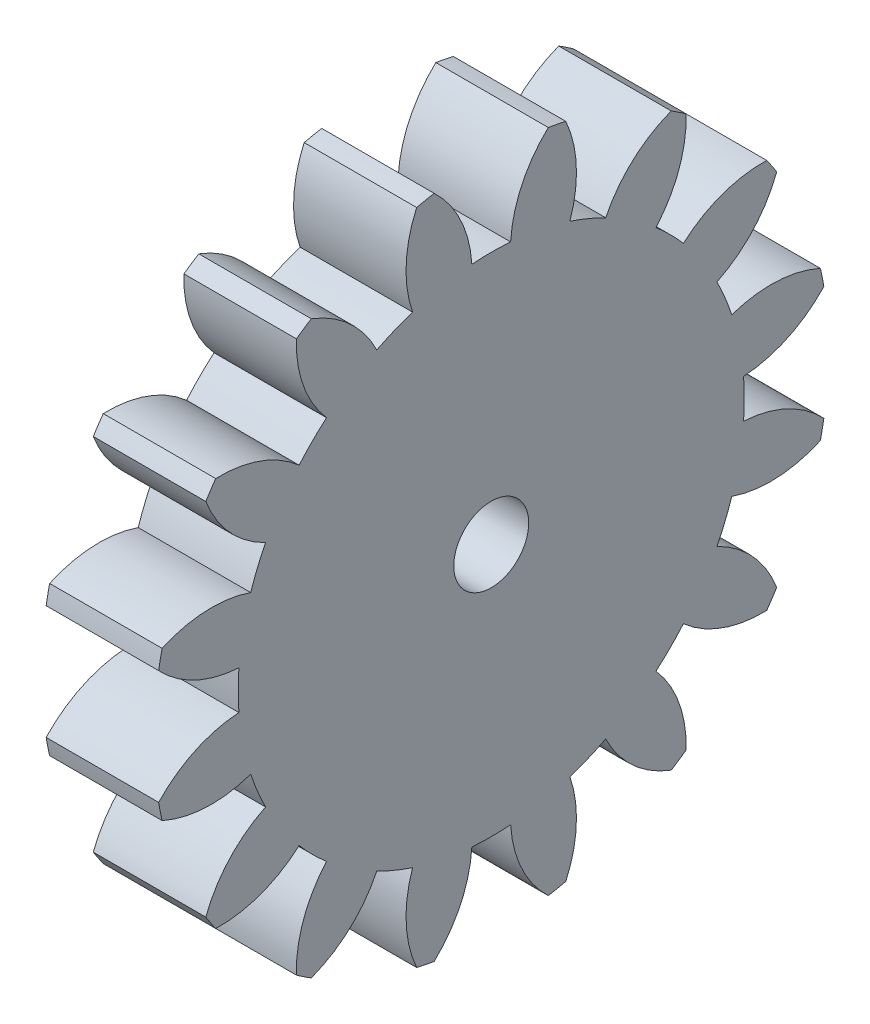
SolidWorks part; units mm, degrees
ref_plane "Plane1" through (0, 0, 0) normal (0, 0, 1) x (1, 0, 0)
ref_plane "Plane2" through (0, 0, 0) normal (0, 1, 0) x (1, 0, 0)
ref_plane "Plane3" through (0, 0, 0) normal (1, 0, 0) x (0, 0, -1)
sketch "HoldingSke" plane through (0, 0, 0) normal (0, 1, 0) x (1, 0, 0)
  line L0 (0, 0) -> (0.4806, -0.1378)
  line L1 (-15, 0) -> (100, 0) construction
  line L2 (0, 0) -> (-2.1039, 2.3779)
  line L3 (0, 0) -> (-11.863, 4.5341)
  line L4 (0, 0) -> (8.3015, 2.3804)
  line L5 (0, 0) -> (-46.8476, -17.4728)
  line L6 (0, 0) -> (-4.9738, -3.3558)
  line L7 (-2.1039, 2.3779) -> (8.6586, 51.2059)
  line L8 (-76.2, 54.61) -> (-75.5, 54.61)
  line L9 (-71.009, 38.7566) -> (-53.1078, 45.2721)
  line L10 (-76.2, 71.12) -> (104.1128, 71.12)
  line L11 (0, 0) -> (-6, 0)
  line L12 (-76.2, 101.6) -> (-76.133, 101.6)
  line L13 (24.9733, 27.94) -> (52.9518, 28.4284)
  line L14 (24.9733, 27.94) -> (24.9743, 27.94)
  line L15 (24.9733, 27.94) -> (100.4006, 29.5858)
  line L16 (-63.627, -2) -> (-12.827, -2)
  circle A0 centre (0, 0) radius 2
  circle A1 centre (0, 0) radius 13.499
  circle A2 centre (0, 0) radius 37.5
  circle A3 centre (0, 0) radius 2
  dimension "MHD" = 26.998
  dimension "Hub_dia" = 75
  dimension "Bore" = 4
  dimension "MBD" = 4
  dimension "Num_teeth" = 16
  dimension "Pitch" = 0.5
  dimension "Overall_len" = 50
  dimension "Show_teeth" = 16
  dimension "Thickness" = 6
  dimension "OAL" = 50.0001
  dimension "T_dim" = 0.7
  dimension "Ap" = 20
  dimension "H" = 19.05
  dimension "Pitch_radius" = 180.3128
  dimension "Width" = 6
  dimension "Backlash" = 0.067
  dimension "Addendum_fac" = 1
  dimension "Dedendum_fac" = 1.25
  dimension "Clearance_fac" = 0.25
  dimension "Dedendum_add" = 0.001
  dimension "Module" = 2
sketch "BasProSke" plane through (0, 0, 0) normal (0, 1, 0) x (1, 0, 0)
  line L0 (-10, 0) -> (60, 0) construction
  line L1 (0, 0) -> (0, 18)
  line L2 (0, 0) -> (6, 0)
  line L3 (6, 0) -> (6, 18)
  line L4 (6, 18) -> (0, 18)
  dimension "Thickness" = 6
  dimension "Diameter" = 36
revolve "Base-Revolve" add sketch "BasProSke" angle 360 about L0
sketch "TooCutSke" plane through (0, 0, 0) normal (1, 0, 0) x (0, 0, -1)
  line L1 (0, 0) -> (0, 107) construction
  line L2 (0, 0) -> (-1.6854, 15.911) construction
  line L3 (0, 0) -> (-6.2172, 31.2558) construction
  line L4 (-1.6854, 15.911) -> (-3.1086, 15.6279) construction
  arc A0 (1.0343, 13.4593) -> (-1.0343, 13.4593) centre (0, 0) ccw
  arc A1 (3.0657, 17.7628) -> (-3.0657, 17.7628) centre (0, 0) ccw
  circle A2 centre (0, 0) radius 16 construction
  circle A3 centre (0, 0) radius 15.0351 construction
  arc A4 (-1.0343, 13.4593) -> (-3.0657, 17.7628) centre (-7.4228, 13.075) ccw
  arc A5 (3.0657, 17.7628) -> (1.0343, 13.4593) centre (7.4228, 13.075) ccw
  dimension "Root_dia" = 26.998
  dimension "Overcut_dia" = 36.0508
  dimension "Pitch_dia" = 32
  dimension "Base_dia" = 30.0702
  dimension "Flank_rad" = 6.4
  dimension "Half_ang" = 11.25
  dimension "Half_CT" = 1.451
extrude "ToothCut" cut sketch "TooCutSke" along normal through all
fillet "Breaks" [suppressed] radius 0.04
fillet "RootFillets" [suppressed] radius 0.501
pattern_circular "TeethCuts" count 16 every 22.5 about axis through (-10, 0, 0) along (1, 0, 0) of "ToothCut", "RootFillets", "Breaks"
sketch "HubNeaOneSke" plane through (0, 0, 0) normal (-1, 0, 0) x (0, 0, 1)
  circle A0 centre (0, 0) radius 13.499
  dimension "Diameter" = 26.998
extrude "HubNearOne" [suppressed] add sketch "HubNeaOneSke" along normal blind 44.0001
sketch "HubNeaBotSke" plane through (0, 0, 0) normal (-1, 0, 0) x (0, 0, 1)
  circle A0 centre (0, 0) radius 13.499
  dimension "Diameter" = 26.998
extrude "HubNearBoth" [suppressed] add sketch "HubNeaBotSke" along normal blind 22
ref_plane "FarPln" through (6, 0, 0) normal (1, 0, 0) x (0, 0, -1)
sketch "HubFarSke" plane through (6, 0, 0) normal (1, 0, 0) x (0, 0, -1)
  circle A0 centre (0, 0) radius 13.499
  dimension "Diameter" = 26.998
extrude "HubFar" [suppressed] add sketch "HubFarSke" along normal blind 22
sketch "BorSke" plane through (0, 0, 0) normal (1, 0, 0) x (0, 0, -1)
  circle A0 centre (0, 0) radius 2
  dimension "Diameter" = 4
extrude "Bore" cut sketch "BorSke" along normal mid plane 100.0001
sketch "KeySke" plane through (0, 0, 0) normal (1, 0, 0) x (0, 0, -1)
  line L0 (-0.8, 0) -> (-0.8, 2.7)
  line L1 (-0.8, 2.7) -> (0.8, 2.7)
  line L2 (0.8, 2.7) -> (0.8, 0)
  line L3 (0, 0) -> (0, 34) construction
  line L4 (-0.8, 0) -> (0.8, 0)
  dimension "Offset" = 2.7
  dimension "Width" = 1.6
extrude "Keyway" [suppressed] cut sketch "KeySke" along normal mid plane 100.0001
pattern_circular "Keyway2" [suppressed] count 2 every 90 about axis through (-10, 0, 0) along (1, 0, 0)
equation "' \"Module@HoldingSke\" = 6.35"
equation "' \"Num_teeth@HoldingSke\" = 12"
equation "' \"Ap@HoldingSke\" =  20"
equation "' \"Ap@HoldingSke\" = 20"
equation "' \"Width@HoldingSke\" = 0.5 * 25.4"
equation "' \"Hub_dia@HoldingSke\"= 1 * 25.4"
equation "' \"Hub_dia@HoldingSke\" = 1 * 25.4"
equation "' \"Overall_len@HoldingSke\" = 1.0 * 25.4"
equation "' \"Bore@HoldingSke\" = 0.75 * 25.4"
equation "' \"T_dim@HoldingSke\" = 0.1 * 25.4"
equation "' \"Width@KeySke\" = 0.25 * 25.4"
equation "' \"Show_teeth@HoldingSke\" = 13"
equation "' \"Backlash@HoldingSke\" = 0.009 * 25.4"
equation "' \"Addendum_fac@HoldingSke\" = 1.0"
equation "' \"Dedendum_fac@HoldingSke\" = 1.25"
equation "' \"Dedendum_add@HoldingSke\" = 0.00005 * 25.4"
equation "' \"Clearance_fac@HoldingSke\" = 0.25"
equation "\"Pitch@HoldingSke\" = 1 / \"Module@HoldingSke\""
equation "\"Overcut_dia@TooCutSke\" = (\"Num_teeth@HoldingSke\" + 2 * \"Addendum_fac@HoldingSke\") / \"Pitch@HoldingSke\" + 0.002 * 25.4"
equation "\"Pitch_dia@TooCutSke\" = \"Num_teeth@HoldingSke\" / \"Pitch@HoldingSke\""
equation "\"Base_dia@TooCutSke\" = \"Num_teeth@HoldingSke\" / \"Pitch@HoldingSke\" * cos((\"Ap@HoldingSke\"  * 3.14159265 / 180))"
equation "\"Root_dia@TooCutSke\" = (\"Num_teeth@HoldingSke\" + 2) / \"Pitch@HoldingSke\" - 2 * (\"Addendum_fac@HoldingSke\" + \"Dedendum_fac@HoldingSke\") / \"Pitch@HoldingSke\" - \"Dedendum_add@HoldingSke\" * 2"
equation "\"Half_ang@TooCutSke\" = 180 / \"Num_teeth@HoldingSke\""
equation "\"Half_CT@TooCutSke\" = \"Num_teeth@HoldingSke\" / \"Pitch@HoldingSke\" * sin((3.14159265 / 2 / \"Num_teeth@HoldingSke\")) / 2 - 7 * \"Backlash@HoldingSke\" / 4"
equation "\"Flank_rad@TooCutSke\" = \"Num_teeth@HoldingSke\" / \"Pitch@HoldingSke\" / 5"
equation "\"Radius@RootFillets\" = \"Clearance_fac@HoldingSke\" / \"Pitch@HoldingSke\" + \"Dedendum_add@HoldingSke\""
equation "\"Break_rad@Breaks\" = 0.02 / \"Pitch@HoldingSke\""
equation "\"Thickness@HoldingSke\" = \"Width@HoldingSke\""
equation "\"OAL@HoldingSke\" = \"Thickness@HoldingSke\""
equation "\"MHD@HoldingSke\" = (\"Num_teeth@HoldingSke\" + 2) / \"Pitch@HoldingSke\" - 2 * (\"Addendum_fac@HoldingSke\" + \"Dedendum_fac@HoldingSke\")  / \"Pitch@HoldingSke\" - \"Dedendum_add@HoldingSke\" * 2"
equation "\"MBD@HoldingSke\" = (\"Num_teeth@HoldingSke\" + 2) / \"Pitch@HoldingSke\" - 2 * (\"Addendum_fac@HoldingSke\" + \"Dedendum_fac@HoldingSke\")  / \"Pitch@HoldingSke\" - \"Dedendum_add@HoldingSke\" * 2 - 0.002 * 25.4"
equation "\"MHD@HoldingSke\" = ((sgn( \"MHD@HoldingSke\" - \"Hub_dia@HoldingSke\" )-1)*( \"MHD@HoldingSke\" - \"Hub_dia@HoldingSke\" ))/-2+ \"Hub_dia@HoldingSke\""
equation "\"MBD@HoldingSke\" = ((sgn( \"MBD@HoldingSke\" - \"Bore@HoldingSke\" )-1)*( \"MBD@HoldingSke\" - \"Bore@HoldingSke\" ))/-2+ \"Bore@HoldingSke\""
equation "\"OAL@HoldingSke\" = ((sgn( \"OAL@HoldingSke\" - \"Overall_len@HoldingSke\" )+1)*( \"OAL@HoldingSke\" - \"Overall_len@HoldingSke\" ))/2 + \"Overall_len@HoldingSke\" + 0.000002 * 25.4"
equation "\"Num_teeth@TeethCuts\" = int( \"Show_teeth@HoldingSke\" ) + 1"
equation "\"Num_teeth@TeethCuts\" = ((sgn( \"Num_teeth@TeethCuts\" - \"Num_teeth@HoldingSke\" )-1)*( \"Num_teeth@TeethCuts\" - \"Num_teeth@HoldingSke\" ))/-2+ \"Num_teeth@HoldingSke\""
equation "\"Num_teeth@TeethCuts\" = ((sgn( \"Num_teeth@TeethCuts\" - 2.0)+1)*( \"Num_teeth@TeethCuts\" - 2.0))/2 +2.0"
equation "\"Angle@TeethCuts\" = 360.0 / \"Num_teeth@HoldingSke\""
equation "\"Diameter@BasProSke\" = (\"Num_teeth@HoldingSke\" + 2 * \"Addendum_fac@HoldingSke\") / \"Pitch@HoldingSke\""
equation "\"Thickness@BasProSke\"  = \"Thickness@HoldingSke\""
equation "' \"Fillet_rad@BasProSke\" =  \"Thickness@HoldingSke\" * 0.05"
equation "' \"Fillet_rad@BasProSke\" = \"Thickness@HoldingSke\" * 0.05"
equation "\"MHD@HoldingSke\" = ((sgn( \"MHD@HoldingSke\" - \"Root_dia@TooCutSke\" )-1)*( \"MHD@HoldingSke\" - \"Root_dia@TooCutSke\" ))/-2+ \"Root_dia@TooCutSke\""
equation "\"Diameter@HubNeaOneSke\" = \"MHD@HoldingSke\""
equation "\"Length@HubNearOne\" = \"OAL@HoldingSke\" - \"Thickness@BasProSke\""
equation "\"Diameter@HubNeaBotSke\" = \"MHD@HoldingSke\""
equation "\"Length@HubNearBoth\" = ( \"OAL@HoldingSke\" - \"Thickness@BasProSke\" ) / 2.0"
equation "\"Thickness@FarPln\" = \"Thickness@BasProSke\""
equation "\"Diameter@HubFarSke\" = \"MHD@HoldingSke\""
equation "\"Length@HubFar\" = ( \"OAL@HoldingSke\" - \"Thickness@BasProSke\" ) / 2.0"
equation "\"Diameter@BorSke\" = \"MBD@HoldingSke\""
equation "\"D1@Bore\" = \"OAL@HoldingSke\" * 2.0"
equation "\"D1@Keyway\" = \"OAL@HoldingSke\" * 2.0"
equation "\"Offset@KeySke\" = \"T_dim@HoldingSke\" + \"MBD@HoldingSke\" / 2.0"
